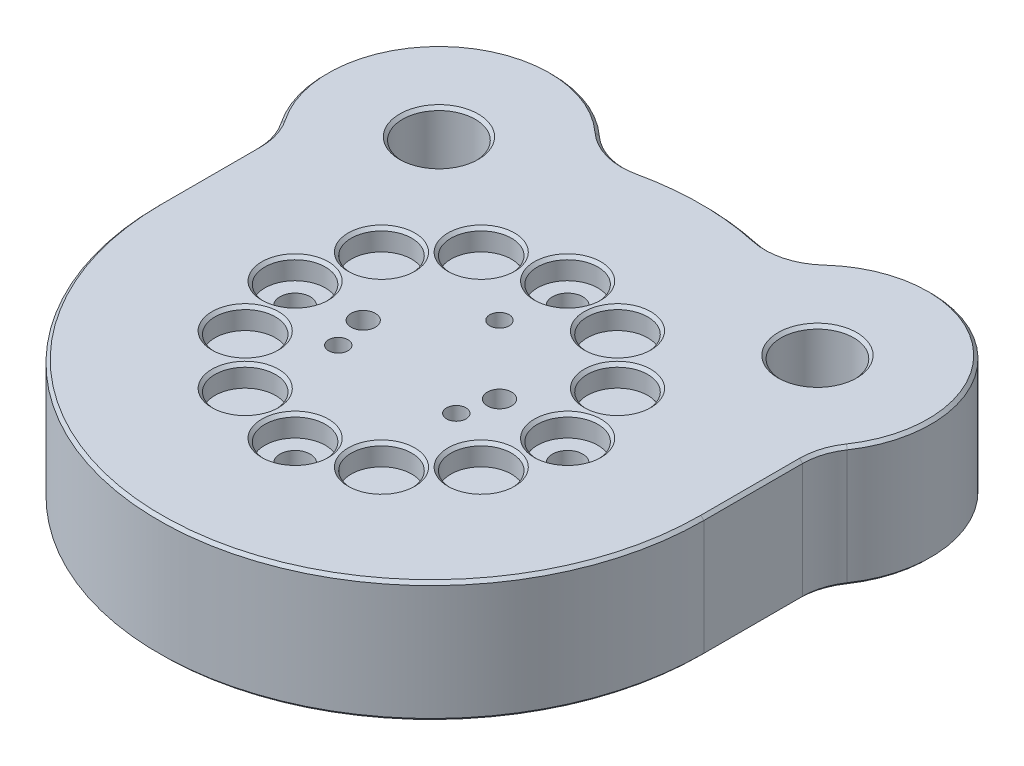
SolidWorks part; units mm, degrees
material "Plain Carbon Steel"
ref_plane "Front Plane" through (0, 0, 0) normal (0, 0, 1) x (1, 0, 0)
ref_plane "Top Plane" through (0, 0, 0) normal (0, 1, 0) x (1, 0, 0)
ref_plane "Right Plane" through (0, 0, 0) normal (1, 0, 0) x (0, 0, -1)
other "Configuration Table"
sketch "Sketch1" plane through (0, 0, 0) normal (0, 1, 0) x (1, 0, 0)
  line L0 (-100, 0) -> (100, 0) construction
  line L1 (0, -100) -> (0, 100) construction
  line L2 (-90, 0) -> (-90, 39.5049)
  line L3 (90, 0) -> (90, 39.5049)
  arc A0 (-90, 0) -> (90, 0) centre (0, 0) ccw
  arc A1 (-30.5618, 84.6521) -> (-90, 39.5049) centre (-62.5, 65) ccw
  arc A2 (90, 39.5049) -> (30.5618, 84.6521) centre (62.5, 65) ccw
  arc A3 (-30.5618, 84.6521) -> (-83.389, 33.8568) centre (0, 0) ccw construction
  arc A4 (-83.389, 33.8568) -> (-30.5618, 84.6521) centre (-62.5, 65) ccw construction
  arc A5 (30.5618, 84.6521) -> (-30.5618, 84.6521) centre (0, 0) ccw
  arc A6 (83.389, 33.8568) -> (30.5618, 84.6521) centre (0, 0) ccw construction
  arc A7 (30.5618, 84.6521) -> (83.389, 33.8568) centre (62.5, 65) ccw construction
  arc A8 (-83.389, 33.8568) -> (-90, 0) centre (0, 0) ccw construction
  arc A9 (90, 0) -> (83.389, 33.8568) centre (0, 0) ccw construction
  arc A10 (-90, 39.5049) -> (-83.389, 33.8568) centre (-62.5, 65) ccw construction
  arc A11 (83.389, 33.8568) -> (90, 39.5049) centre (62.5, 65) ccw construction
  dimension "D3" = 180
  dimension "D4" = 75
  dimension "D1" = 200
  dimension "D2" = 200
  dimension "D5" = 65
  dimension "D6" = 125
extrude "Boss-Extrude1" add sketch "Sketch1" against normal blind 40
sketch "Sketch2" plane through (0, 0, 0) normal (0, 1, 0) x (1, 0, 0)
  line L0 (-81.25, 32.524) -> (-59.2695, 19.8336)
  line L1 (-90, 39.5049) -> (-90, 0) construction
  line L2 (-90, 39.5049) -> (-90, 0)
  line L3 (0, -62.5) -> (0, 62.5) construction
  line L4 (81.25, 32.524) -> (59.2695, 19.8336)
  line L5 (90, 0) -> (90, 39.5049) construction
  line L6 (90, 0) -> (90, 39.5049)
  arc A0 (-59.2695, 19.8336) -> (59.2695, 19.8336) centre (0, 0) ccw
  arc A1 (-30.5618, 84.6521) -> (-90, 39.5049) centre (-62.5, 65) ccw construction
  arc A2 (-90, 39.5049) -> (-81.25, 32.524) centre (-62.5, 65) ccw
  arc A3 (-81.25, 32.524) -> (-69.2916, 28.1201) centre (-62.5, 65) ccw construction
  arc A4 (-30.5618, 84.6521) -> (-90, 39.5049) centre (-62.5, 65) ccw construction
  arc A5 (-90, 0) -> (90, 0) centre (0, 0) ccw construction
  arc A6 (-90, 0) -> (90, 0) centre (0, 0) ccw
  arc A7 (90, 39.5049) -> (81.25, 32.524) centre (62.5, 65) cw
  arc A8 (0, 62.5) -> (-59.2695, 19.8336) centre (0, 0) ccw construction
  arc A9 (59.2695, 19.8336) -> (0, 62.5) centre (0, 0) ccw construction
  dimension "D1" = 125
  dimension "D2" = 60
fillet "Fillet1" radius 20 4 edges at (30.5618, -20, -84.6521) (-30.5618, -20, -84.6521) (90, -20, -39.5049) (-90, -20, -39.5049)
sketch "Sketch3" plane through (0, 0, 0) normal (0, 1, 0) x (1, 0, 0)
  circle A0 centre (-62.5, 65) radius 12
  circle A1 centre (62.5, 65) radius 12
  dimension "D1" = 24
extrude "Cut-Extrude2" cut sketch "Sketch3" against normal up to next
sketch "Sketch4" plane through (0, 0, 0) normal (0, 1, 0) x (1, 0, 0)
  circle A0 centre (0, 0) radius 45 construction
  circle A1 centre (0, 45) radius 10
  dimension "D1" = 90
  dimension "D2" = 20
extrude "Cut-Extrude3" cut sketch "Sketch4" against normal blind 7
pattern_circular "CirPattern1" count 12 over 360 about axis through (0, 0, 0) along (0, 1, 0) of "Cut-Extrude3"
hole_wizard "Ø10.0 (10) Diameter Hole1" positions "Sketch7" profile "Sketch6" hole size "Ø10.0" standard "ISO" end condition through all
sketch "Sketch7" plane through (0, 0, 0) normal (0, 1, 0) x (1, 0, 0)
  point P0 (0, 45)
  point P3 (45, 0)
  point P6 (0, -45)
  point P9 (-45, 0)
sketch "Sketch6" plane through (0, 0, -45) normal (1, 0, 0) x (0, 0, 1)
  line L0 (0, 0) -> (0, 40)
  line L1 (0, 40) -> (5, 40)
  line L2 (5, 40) -> (5, 0)
  line L5 (5, 0) -> (0, 0)
  line L11 (0, -6.35) -> (0, 107.95) construction
  dimension "Thru Hole Dia." = 10
  dimension "Thru Hole Depth" = 40
sketch "Sketch8" plane through (0, -40, 0) normal (0, -1, 0) x (1, 0, 0)
  circle A0 centre (0, 45) radius 8.5
  circle A1 centre (45, 0) radius 8.5
  circle A2 centre (0, -45) radius 8.5
  circle A3 centre (-45, 0) radius 8.5
  dimension "D1" = 17
extrude "Cut-Extrude4" cut sketch "Sketch8" against normal blind 23
hole_wizard "CBORE for M6 Hex Socket Head Cap Screw1" positions "Sketch14" profile "Sketch13" counterbore size "M6" standard "ISO" end condition through all
sketch "Sketch14" plane through (0, -40, 0) normal (0, -1, 0) x (-1, 0, 0)
  point P0 (0, 22.5)
  point P3 (-19.4856, -11.25)
  point P6 (19.4856, -11.25)
sketch "Sketch13" plane through (0, -40, -22.5) normal (1, 0, 0) x (0, 0, -1)
  line L0 (0, 0) -> (0, 40)
  line L1 (0, 40) -> (3.2, 40)
  line L3 (3.2, 40) -> (3.2, 6.4)
  line L4 (3.2, 6.4) -> (5.5, 6.4)
  line L5 (5.5, 6.4) -> (5.5, 0)
  line L7 (5.5, 0) -> (0, 0)
  line L11 (0, -6.35) -> (0, 107.95) construction
  dimension "Thru Hole Dia." = 6.4
  dimension "Thru Hole Depth" = 40
  dimension "C'Bore Dia." = 11
  dimension "C'Bore Depth" = 6.4
hole_wizard "Ø8.0mm Dowel Hole1" positions "Sketch17" profile "Sketch16" hole size "Ø8.0" standard "ISO" end condition through all
sketch "Sketch17" plane through (0, 0, 0) normal (0, 1, 0) x (1, 0, 0)
  point P0 (-22.5, 0)
  point P3 (22.5, 0)
sketch "Sketch16" plane through (-22.5, 0, 0) normal (1, 0, 0) x (0, 0, 1)
  line L0 (0, 0) -> (0, 40)
  line L1 (0, 40) -> (4, 40)
  line L2 (4, 40) -> (4, 0)
  line L5 (4, 0) -> (0, 0)
  line L11 (0, -6.35) -> (0, 107.95) construction
  dimension "Thru Hole Dia." = 8
  dimension "Thru Hole Depth" = 40
chamfer "Chamfer1" distance 1 angle 45 24 edges at (-62.5, -40, -53) (62.5, -40, -53) (-62.5, 0, -53) (62.5, 0, -53) (0, -40, -90) (-28.8639, -40, -88.103) (28.8639, -40, -88.103) (-87.0629, -40, -93.3358) (87.0629, -40, -93.3358) (-90.8893, -40, -38.494) (90.8893, -40, -38.494) (-90, -40, -16.2981) (90, -40, -16.2981) (0, -40, 90) (0, 0, -90) (-28.8639, 0, -88.103) (28.8639, 0, -88.103) (-87.0629, 0, -93.3358) (87.0629, 0, -93.3358) (-90.8893, 0, -38.494) (90.8893, 0, -38.494) (-90, 0, -16.2981) (90, 0, -16.2981) (0, 0, 90)
chamfer "Chamfer2" distance 0.5 angle 45 4 edges at (-45, -40, -8.5) (0, -40, -53.5) (45, -40, -8.5) (0, -40, 36.5)
chamfer "Chamfer3" distance 1 angle 45 12 edges at (-35, 0, 0) (-30.3109, 0, 17.5) (-17.5, 0, 30.3109) (0, 0, 35) (17.5, 0, 30.3109) (30.3109, 0, 17.5) (35, 0, 0) (30.3109, 0, -17.5) (17.5, 0, -30.3109) (0, 0, -35) (-17.5, 0, -30.3109) (-30.3109, 0, -17.5)
